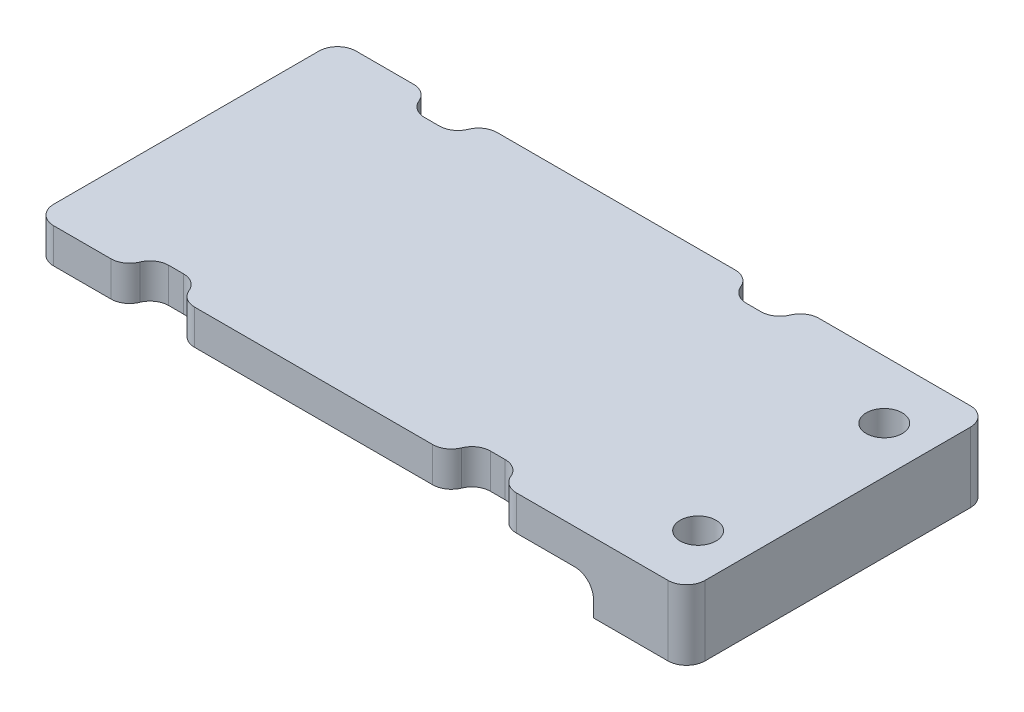
SolidWorks part; units mm, degrees
ref_plane "Front" through (0, 0, 0) normal (0, 0, 1) x (1, 0, 0)
ref_plane "Top" through (0, 0, 0) normal (0, 1, 0) x (1, 0, 0)
ref_plane "Right" through (0, 0, 0) normal (1, 0, 0) x (0, 0, -1)
sketch "Sketch1" plane through (0, 0, 0) normal (0, 1, 0) x (1, 0, 0)
  line L1 (-44.45, -20.6375) -> (44.45, -20.6375)
  line L2 (-44.45, -20.6375) -> (-44.45, 20.6375)
  line L3 (-44.45, 20.6375) -> (44.45, 20.6375)
  line L4 (44.45, -20.6375) -> (44.45, 20.6375)
  line L5 (-44.45, -20.6375) -> (44.45, 20.6375) construction
  line L6 (-44.45, 20.6375) -> (44.45, -20.6375) construction
  point P0 (0, 0)
  dimension "D1" = 88.9
  dimension "D2" = 41.275
extrude "Boss-Extrude1" add sketch "Sketch1" along normal blind 4.7625
sketch "Sketch3" plane through (0, 0, 0) normal (0, -1, 0) x (1, 0, 0)
  line L0 (44.45, -20.6375) -> (-44.45, -20.6375) construction
  line L1 (44.45, 20.6375) -> (31.75, 20.6375)
  line L2 (44.45, 20.6375) -> (44.45, -20.6375)
  line L3 (44.45, -20.6375) -> (31.75, -20.6375)
  line L4 (31.75, 20.6375) -> (31.75, -20.6375)
  dimension "D1" = 12.7
extrude "Boss-Extrude2" add sketch "Sketch3" along normal blind 4.7625
sketch "Sketch8" plane through (0, 4.7625, 0) normal (0, 1, 0) x (1, 0, 0)
  line L4 (44.45, -20.6375) -> (44.45, 20.6375) construction
  line L5 (-50, 0) -> (50, 0) construction
  point P0 (38.1, 12.7)
  point P4 (38.1, -12.7)
  dimension "D1" = 25.4
  dimension "D2" = 12.7
  dimension "D3" = 6.35
hole_wizard "#10 (0.1935) Diameter Hole1" positions "Sketch8" profile "Sketch7" hole size "#10" standard "ANSI Inch" end condition through all
sketch "Sketch7" plane through (38.1, 4.7625, -12.7) normal (1, 0, 0) x (0, 0, 1)
  line L0 (0, 0) -> (0, 9.525)
  line L1 (0, 9.525) -> (2.4574, 9.525)
  line L2 (2.4574, 9.525) -> (2.4574, 0)
  line L5 (2.4574, 0) -> (0, 0)
  line L11 (0, -6.35) -> (0, 107.95) construction
  dimension "Thru Hole Dia." = 4.9149
  dimension "Thru Hole Depth" = 9.525
sketch "Sketch9" plane through (0, 4.7625, 0) normal (0, 1, 0) x (1, 0, 0)
  line L14 (44.45, 20.6375) -> (-44.45, 20.6375) construction
  line L20 (12.3597, 20.6375) -> (18.7097, 20.6375)
  line L21 (12.3597, 20.6375) -> (12.3597, 17.4625)
  line L22 (12.3597, 17.4625) -> (18.7097, 17.4625)
  line L23 (18.7097, 20.6375) -> (18.7097, 17.4625)
  line L24 (-44.45, -20.6375) -> (44.45, -20.6375) construction
  line L25 (-31.5516, 20.6375) -> (-25.2016, 20.6375)
  line L26 (-31.5516, 20.6375) -> (-31.5516, 17.4625)
  line L27 (-31.5516, 17.4625) -> (-25.2016, 17.4625)
  line L28 (-25.2016, 20.6375) -> (-25.2016, 17.4625)
  line L29 (-31.5516, -20.6375) -> (-25.2016, -20.6375)
  line L30 (-31.5516, -20.6375) -> (-31.5516, -17.4625)
  line L31 (-31.5516, -17.4625) -> (-25.2016, -17.4625)
  line L32 (-25.2016, -20.6375) -> (-25.2016, -17.4625)
  line L34 (12.3597, -20.6375) -> (18.7097, -20.6375)
  line L35 (12.3597, -20.6375) -> (12.3597, -17.4625)
  line L36 (12.3597, -17.4625) -> (18.7097, -17.4625)
  line L37 (18.7097, -20.6375) -> (18.7097, -17.4625)
  line L38 (44.45, -20.6375) -> (44.45, 20.6375) construction
  dimension "D1" = 3.175
  dimension "D2" = 6.35
  dimension "D3" = 37.5613
  dimension "D4" = 76.0016
extrude "Cut-Extrude1" cut sketch "Sketch9" against normal through all
fillet "Fillet1" radius 2.54 13 edges at (31.75, 0, 0) (12.3597, 2.3812, 20.6375) (18.7097, 2.3812, 20.6375) (-31.5516, 2.3812, 20.6375) (-25.2016, 2.3812, 20.6375) (44.45, 0, 20.6375) (-44.45, 2.3813, 20.6375) (-31.5516, 2.3812, -20.6375) (-25.2016, 2.3812, -20.6375) (-44.45, 2.3813, -20.6375) (44.45, 0, -20.6375) (12.3597, 2.3812, -20.6375) (18.7097, 2.3812, -20.6375)
fillet "Fillet2" radius 2.54 8 edges at (18.7097, 2.3813, -17.4625) (12.3597, 2.3812, -17.4625) (-31.5516, 2.3812, -17.4625) (-25.2016, 2.3813, -17.4625) (-25.2016, 2.3813, 17.4625) (-31.5516, 2.3812, 17.4625) (12.3597, 2.3812, 17.4625) (18.7097, 2.3813, 17.4625)
